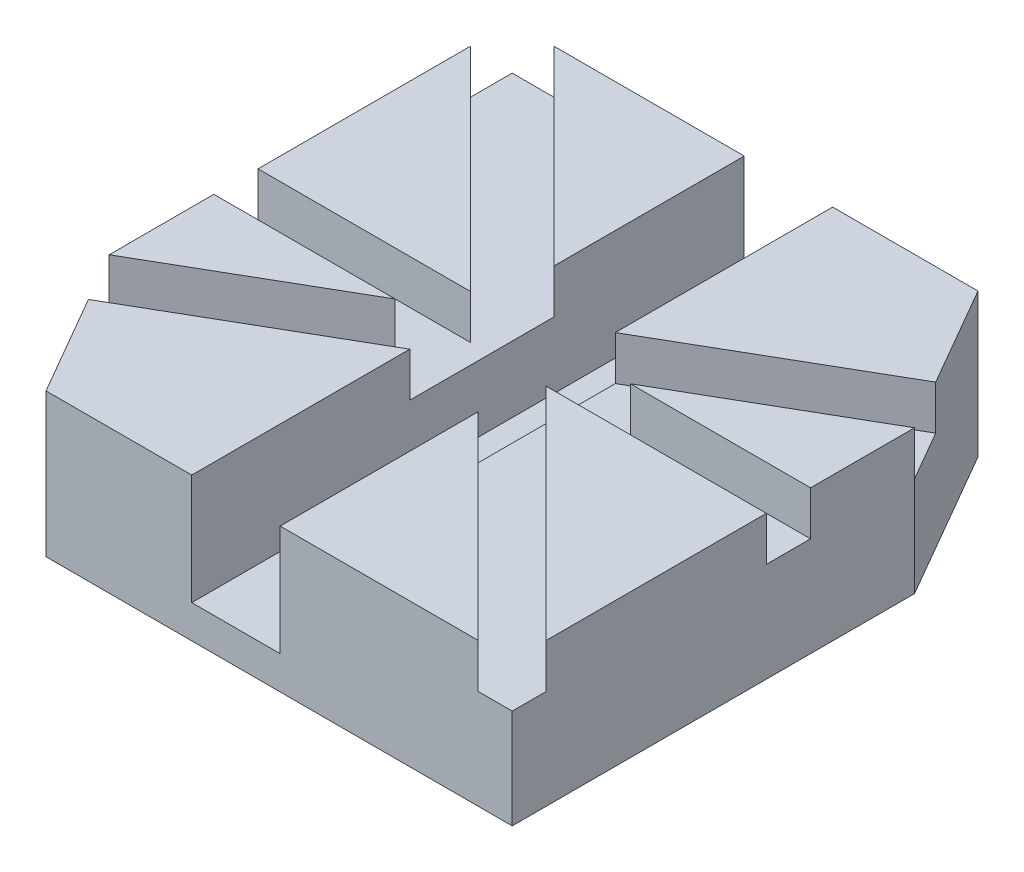
SolidWorks part; units mm, degrees
ref_plane "前视基准面" through (0, 0, 0) normal (0, 0, 1) x (1, 0, 0)
ref_plane "上视基准面" through (0, 0, 0) normal (0, 1, 0) x (1, 0, 0)
ref_plane "右视基准面" through (0, 0, 0) normal (1, 0, 0) x (0, 0, -1)
other "Configuration Table"
sketch "草图2" plane through (0, 0, 0) normal (0, 1, 0) x (1, 0, 0)
  line L1 (-25, -25) -> (25, -25)
  line L2 (-25, -25) -> (-25, 25)
  line L3 (-25, 25) -> (25, 25)
  line L4 (25, -25) -> (25, 25)
  line L5 (-25, -25) -> (25, 25) construction
  line L6 (-25, 25) -> (25, -25) construction
  point P0 (0, 0)
  dimension "D1" = 50
  dimension "D2" = 50
extrude "凸台-拉伸1" add sketch "草图2" along normal blind 13
sketch "草图3" plane through (0, 13, 0) normal (0, 1, 0) x (1, 0, 0)
  line L0 (-25, -25) -> (25, -25) construction
  line L1 (-4, 25) -> (4, 25)
  line L2 (-4, 25) -> (-4, -25)
  line L3 (-4, -25) -> (4, -25)
  line L4 (4, 25) -> (4, -25)
  line L5 (-4, 25) -> (4, -25) construction
  line L6 (-4, -25) -> (4, 25) construction
  point P0 (0, 0)
  dimension "D1" = 8
extrude "切除-拉伸1" cut sketch "草图3" against normal blind 10
sketch "草图4" plane through (0, 13, 0) normal (0, 1, 0) x (1, 0, 0)
  line L0 (25, -25) -> (25, 25) construction
  line L1 (-25, 2) -> (25, 2)
  line L2 (-25, 2) -> (-25, -2)
  line L3 (-25, -2) -> (25, -2)
  line L4 (25, 2) -> (25, -2)
  line L5 (-25, 2) -> (25, -2) construction
  line L6 (-25, -2) -> (25, 2) construction
  point P0 (0, 0)
  dimension "D1" = 4
extrude "切除-拉伸2" cut sketch "草图4" against normal blind 4
sketch "草图5" plane through (0, 13, 0) normal (0, 1, 0) x (1, 0, 0)
  line L0 (-1.2823, 2.221) -> (1.2823, -2.221)
  line L1 (1.2823, -2.221) -> (-26.1999, -18.0878)
  line L2 (-26.1999, -18.0878) -> (-28.7644, -13.6459)
  line L3 (-28.7644, -13.6459) -> (-1.2823, 2.221)
  line L4 (-25, -2) -> (-4, -2) construction
  point P4 (0, 0)
  dimension "D1" = 30
extrude "切除-拉伸4" cut sketch "草图5" against normal blind 4
sketch "草图7" plane through (0, 13, 0) normal (0, 1, 0) x (1, 0, 0)
  line L0 (-1.8814, -1.8814) -> (1.8814, 1.8814)
  line L1 (1.8814, 1.8814) -> (-24.7246, 28.4874)
  line L2 (-24.7246, 28.4874) -> (-28.4874, 24.7246)
  line L3 (-28.4874, 24.7246) -> (-1.8814, -1.8814)
  line L4 (-4, 2) -> (-25, 2) construction
  point P4 (0, 0)
  dimension "D1" = 45
extrude "切除-拉伸5" cut sketch "草图7" against normal blind 4
sketch "草图8" plane through (0, 13, 0) normal (0, 1, 0) x (1, 0, 0)
  line L0 (-1.5408, -1.5408) -> (1.5408, 1.5408)
  line L1 (1.5408, 1.5408) -> (29.9085, -26.8269)
  line L2 (29.9085, -26.8269) -> (26.8269, -29.9085)
  line L3 (26.8269, -29.9085) -> (-1.5408, -1.5408)
  line L4 (4, -2) -> (25, -2) construction
  point P4 (0, 0)
  dimension "D1" = 45
extrude "切除-拉伸6" cut sketch "草图8" against normal blind 4
sketch "草图9" plane through (0, 13, 0) normal (0, 1, 0) x (1, 0, 0)
  line L0 (-1.3091, 2.2675) -> (1.3091, -2.2675)
  line L1 (1.3091, -2.2675) -> (34.2091, 16.7274)
  line L2 (34.2091, 16.7274) -> (31.5909, 21.2623)
  line L3 (31.5909, 21.2623) -> (-1.3091, 2.2675)
  line L4 (25, 2) -> (4, 2) construction
  point P4 (0, 0)
  dimension "D1" = 30
extrude "切除-拉伸7" cut sketch "草图9" against normal blind 4
sketch "草图10" plane through (0, 13, 0) normal (0, 1, 0) x (1, 0, 0)
  line L0 (-25, -11.4725) -> (-17.1899, -25)
  line L1 (-25, -2) -> (-25, -11.4725) construction
  line L2 (-25, -17.395) -> (-25, -11.4725) construction
  line L3 (-25, -25) -> (-4, -25) construction
  line L4 (-17.1899, -25) -> (-25, -25)
  line L5 (-25, -25) -> (-25, -11.4725)
  line L6 (25, 11.4105) -> (17.1541, 25)
  line L7 (25, 25) -> (4, 25) construction
  line L8 (17.1541, 25) -> (25, 25)
  line L9 (25, 25) -> (25, 11.4105)
  dimension "D1" = 60
  dimension "D2" = 60
extrude "切除-拉伸8" cut sketch "草图10" against normal through all
